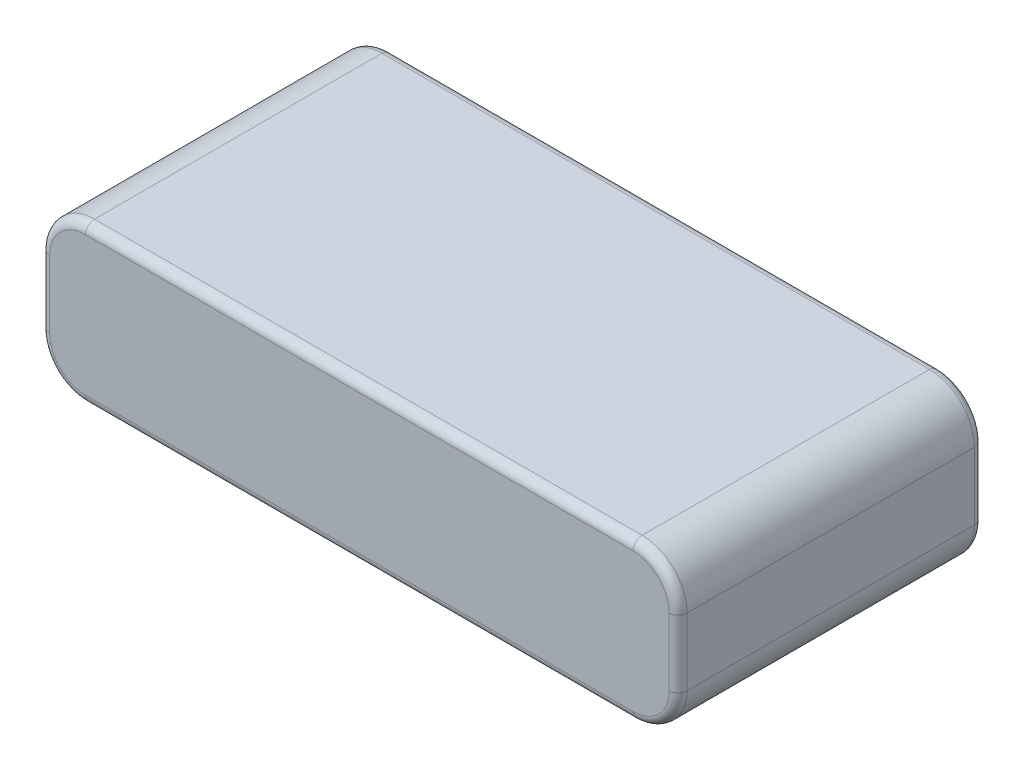
SolidWorks part; units mm, degrees
ref_plane "前视基准面" through (0, 0, 0) normal (0, 0, 1) x (1, 0, 0)
ref_plane "上视基准面" through (0, 0, 0) normal (0, 1, 0) x (1, 0, 0)
ref_plane "右视基准面" through (0, 0, 0) normal (1, 0, 0) x (0, 0, -1)
sketch "草图1" plane through (0, 0, 0) normal (0, 1, 0) x (1, 0, 0)
  line L1 (35.5, -17) -> (-35.5, -17)
  line L2 (35.5, -17) -> (35.5, 17)
  line L3 (35.5, 17) -> (-35.5, 17)
  line L4 (-35.5, -17) -> (-35.5, 17)
  line L5 (35.5, -17) -> (-35.5, 17) construction
  line L6 (35.5, 17) -> (-35.5, -17) construction
  point P0 (0, 0)
  dimension "D1" = 71
  dimension "D2" = 34
extrude "凸台-拉伸1" add sketch "草图1" along normal blind 17.5
fillet "圆角1" radius 5 4 edges at (-35.5, 0, 0) (35.5, 0, 0) (35.5, 17.5, 0) (-35.5, 17.5, 0)
fillet "圆角2" radius 1 16 edges at (34.0355, 1.4645, -17) (35.5, 8.75, -17) (34.0355, 16.0355, -17) (0, 17.5, -17) (-34.0355, 16.0355, -17) (-35.5, 8.75, -17) (-34.0355, 1.4645, -17) (0, 0, -17) (-34.0355, 16.0355, 17) (0, 17.5, 17) (34.0355, 16.0355, 17) (35.5, 8.75, 17) (34.0355, 1.4645, 17) (0, 0, 17) (-34.0355, 1.4645, 17) (-35.5, 8.75, 17)
